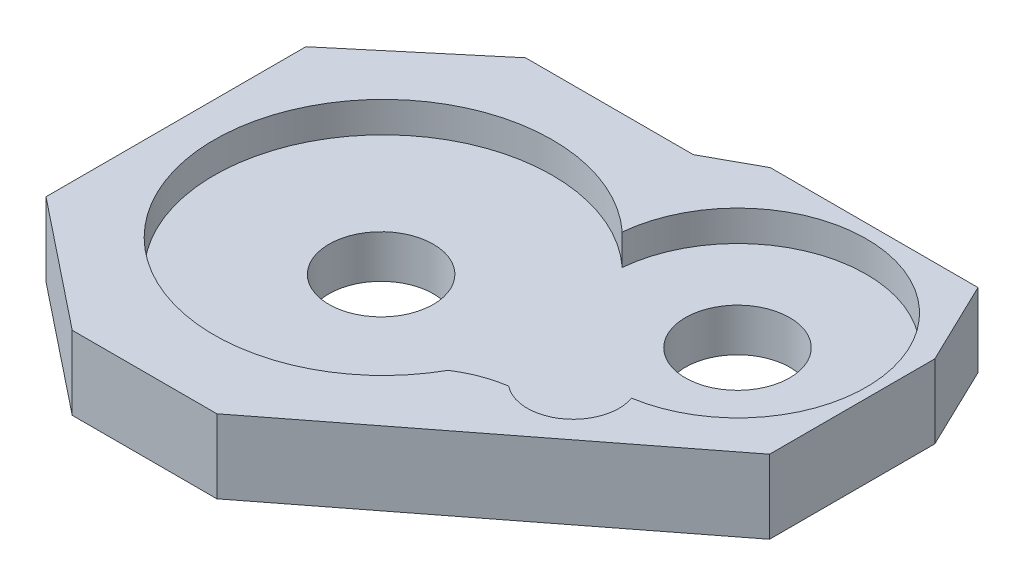
SolidWorks part; units mm, degrees
ref_plane "Спереди" through (0, 0, 0) normal (0, 0, 1) x (1, 0, 0)
ref_plane "Сверху" through (0, 0, 0) normal (0, 1, 0) x (1, 0, 0)
ref_plane "Справа" through (0, 0, 0) normal (1, 0, 0) x (0, 0, -1)
sketch "Эскиз1" plane through (0, 0, 0) normal (0, 1, 0) x (1, 0, 0)
  line L0 (55.1853, -46.649) -> (38.9784, -59.2086) construction
  line L1 (41.2343, 16.1393) -> (49.3313, 20.5764)
  line L2 (-5.5385, -0.1892) -> (-5.5385, -42.5147)
  line L3 (83.1597, 20.5764) -> (89.6959, 7.0048)
  line L4 (38.9784, -59.2086) -> (89.6959, -19.9049)
  line L5 (38.9784, -59.2086) -> (15.4262, -59.2086)
  line L10 (89.6959, -19.9049) -> (89.6959, 7.0048)
  line L11 (83.1597, 20.5764) -> (49.3313, 20.5764)
  line L12 (15.4262, -59.2086) -> (-5.5385, -42.5147)
  line L13 (41.2343, 16.1393) -> (13.9144, 16.1393)
  line L14 (13.9144, 16.1393) -> (-5.5385, -0.1892)
extrude "Вытянуть1" add sketch "Эскиз1" along normal blind 12 from offset 2
sketch "Эскиз2" plane through (0, 10, 0) normal (0, 1, 0) x (1, 0, 0)
  arc A0 (46.3534, -0.5587) -> (51.6919, -34.2464) centre (27.6643, -20.7872) ccw
  arc A1 (70.5607, -23.235) -> (46.3534, -0.5587) centre (67.1896, -2.5747) ccw
  arc A2 (58.8433, -31.5412) -> (70.5607, -23.235) centre (63.4945, -25.6847) ccw
  arc A3 (51.6919, -34.2464) -> (58.8433, -31.5412) centre (61.4765, -49.3075) cw
extrude "Вырез-Вытянуть1" cut sketch "Эскиз2" against normal blind 5
sketch "Эскиз4" plane through (0, -2, 0) normal (0, -1, 0) x (1, 0, 0)
  circle A0 centre (27.6886, 21.1628) radius 8.5
  circle A1 centre (67.0689, 2.4982) radius 8.5
extrude "Вырез-Вытянуть2" cut sketch "Эскиз4" against normal through all
